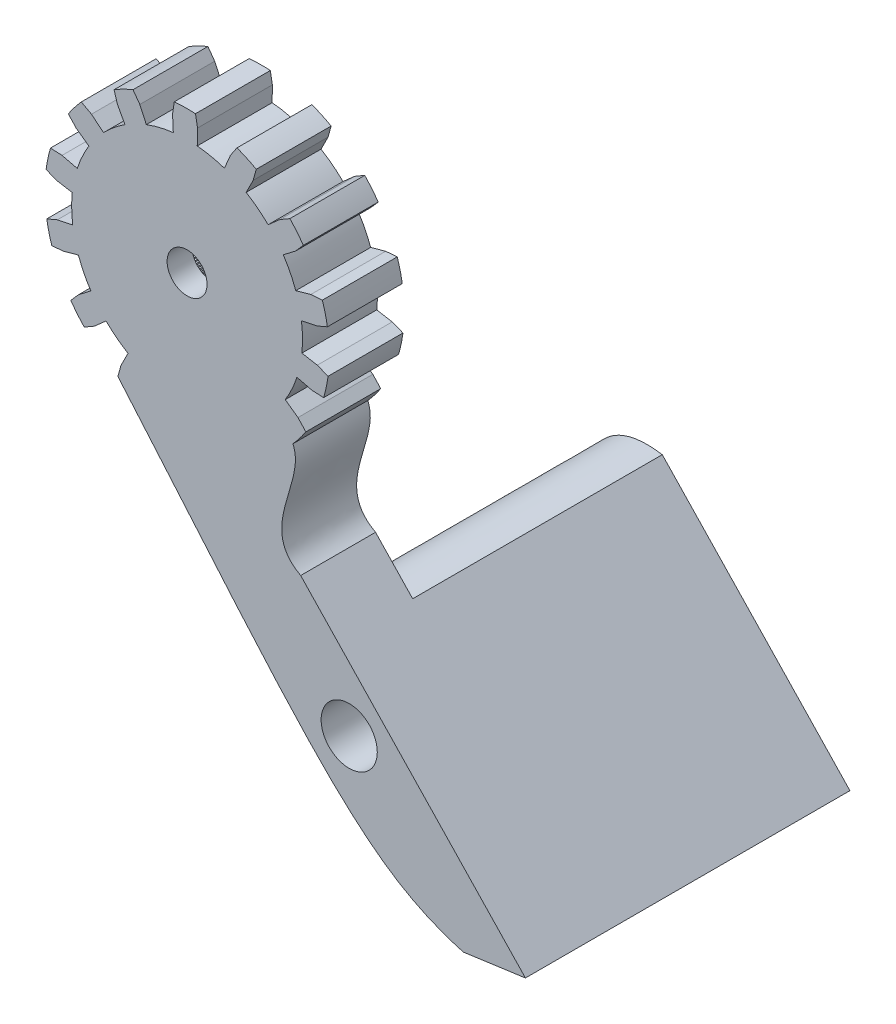
SolidWorks part; units mm, degrees
ref_plane "Front Plane" through (0, 0, 0) normal (0, 0, 1) x (1, 0, 0)
ref_plane "Top Plane" through (0, 0, 0) normal (0, 1, 0) x (1, 0, 0)
ref_plane "Right Plane" through (0, 0, 0) normal (1, 0, 0) x (0, 0, -1)
sketch "Sketch2" plane through (0, 0, 0) normal (0, 0, 1) x (1, 0, 0)
  line L0 (11.1946, 10) -> (11.1946, 10.6054) construction
  line L669 (17.6878, 7.31) -> (18.6279, 8.138)
  line L670 (18.6279, 8.138) -> (19.4304, 8.6044)
  line L671 (21.6272, -0.4657) -> (22.4922, -0.8024)
  line L672 (20.3937, -0.247) -> (21.6272, -0.4657)
  line L673 (20.3589, 1.9784) -> (21.5849, 2.2356)
  line L674 (21.5849, 2.2356) -> (22.439, 2.5991)
  line L675 (21.1094, 4.1784) -> (22.0348, 4.2505)
  line L676 (19.9032, 3.8403) -> (21.1094, 4.1784)
  line L677 (18.9062, 5.8303) -> (19.8993, 6.5939)
  line L678 (19.8993, 6.5939) -> (20.511, 7.292)
  line L679 (14.4587, -7.9329) -> (14.9822, -9.071)
  line L680 (14.9822, -9.071) -> (15.5266, -9.8227)
  line L681 (16.7705, -8.175) -> (17.0467, -9.0612)
  line L682 (16.1724, -7.0743) -> (16.7705, -8.175)
  line L683 (17.8907, -5.6595) -> (18.8561, -6.4578)
  line L684 (18.8561, -6.4578) -> (19.6729, -6.8988)
  line L685 (20.0786, -4.8746) -> (20.7119, -5.5532)
  line L686 (19.0622, -4.1424) -> (20.0786, -4.8746)
  line L687 (19.9964, -2.1222) -> (21.2126, -2.4225)
  line L688 (21.2126, -2.4225) -> (22.1398, -2.4655)
  line L689 (3.4829, -4.3861) -> (2.4899, -5.1497)
  line L690 (2.4899, -5.1497) -> (1.8781, -5.8478)
  line L691 (3.7613, -6.6939) -> (2.9588, -7.1603)
  line L692 (4.7013, -5.8658) -> (3.7613, -6.6939)
  line L693 (6.463, -7.2262) -> (5.8996, -8.3451)
  line L694 (5.8996, -8.3451) -> (5.6513, -9.2394)
  line L695 (7.7151, -9.1846) -> (7.1944, -9.953)
  line L696 (8.2027, -8.0307) -> (7.7151, -9.1846)
  line L697 (10.3802, -8.492) -> (10.3581, -9.7445)
  line L698 (10.3581, -9.7445) -> (10.5224, -10.6581)
  line L699 (12.358, -9.7133) -> (12.2223, -10.6315)
  line L700 (12.2967, -8.462) -> (12.358, -9.7133)
  line L701 (2.3105, 6.3188) -> (1.6772, 6.9974)
  line L702 (3.327, 5.5866) -> (2.3105, 6.3188)
  line L703 (2.3927, 3.5664) -> (1.1765, 3.8667)
  line L704 (1.1765, 3.8667) -> (0.2493, 3.9097)
  line L705 (0.762, 1.9099) -> (-0.103, 2.2465)
  line L706 (1.9955, 1.6912) -> (0.762, 1.9099)
  line L707 (2.0303, -0.5343) -> (0.8042, -0.7914)
  line L708 (0.8042, -0.7914) -> (-0.0498, -1.1549)
  line L709 (1.2798, -2.7343) -> (0.3543, -2.8063)
  line L710 (2.486, -2.3961) -> (1.2798, -2.7343)
  line L711 (12.009, 9.9362) -> (12.0311, 11.1887)
  line L712 (12.0311, 11.1887) -> (11.8667, 12.1023)
  line L713 (10.0311, 11.1574) -> (10.1668, 12.0757)
  line L714 (10.0924, 9.9062) -> (10.0311, 11.1574)
  line L715 (7.9305, 9.377) -> (7.4069, 10.5151)
  line L716 (7.4069, 10.5151) -> (6.8625, 11.2669)
  line L717 (5.6186, 9.6192) -> (5.3425, 10.5054)
  line L718 (6.2167, 8.5185) -> (5.6186, 9.6192)
  line L719 (4.4985, 7.1037) -> (3.533, 7.9019)
  line L720 (3.533, 7.9019) -> (2.7163, 8.343)
  line L721 (15.9262, 8.6703) -> (16.4895, 9.7892)
  line L722 (16.4895, 9.7892) -> (16.7378, 10.6836)
  line L723 (14.6741, 10.6288) -> (15.1948, 11.3972)
  line L724 (14.1864, 9.4749) -> (14.6741, 10.6288)
  arc A141 (20.511, 7.292) -> (19.4304, 8.6044) centre (11.1946, 0.7221) ccw
  arc A145 (17.6878, 7.31) -> (15.9262, 8.6703) centre (11.1946, 0.7221) ccw
  arc A149 (22.439, 2.5991) -> (22.0348, 4.2505) centre (11.1946, 0.7221) ccw
  arc A151 (22.1398, -2.4655) -> (22.4922, -0.8024) centre (11.1946, 0.7221) ccw
  arc A152 (19.6729, -6.8988) -> (20.7119, -5.5532) centre (11.1946, 0.7221) ccw
  arc A153 (15.5266, -9.8227) -> (17.0467, -9.0612) centre (11.1946, 0.7221) ccw
  arc A154 (10.5224, -10.6581) -> (12.2223, -10.6315) centre (11.1946, 0.7221) ccw
  arc A155 (5.6513, -9.2394) -> (7.1944, -9.953) centre (11.1946, 0.7221) ccw
  arc A156 (1.8781, -5.8478) -> (2.9588, -7.1603) centre (11.1946, 0.7221) ccw
  arc A157 (-0.0498, -1.1549) -> (0.3543, -2.8063) centre (11.1946, 0.7221) ccw
  arc A158 (0.2493, 3.9097) -> (-0.103, 2.2465) centre (11.1946, 0.7221) ccw
  arc A159 (2.7163, 8.343) -> (1.6772, 6.9974) centre (11.1946, 0.7221) ccw
  arc A160 (6.8625, 11.2669) -> (5.3425, 10.5054) centre (11.1946, 0.7221) ccw
  arc A161 (11.8667, 12.1023) -> (10.1668, 12.0757) centre (11.1946, 0.7221) ccw
  arc A162 (16.7378, 10.6836) -> (15.1948, 11.3972) centre (11.1946, 0.7221) ccw
  arc A163 (19.9032, 3.8403) -> (18.9062, 5.8303) centre (11.1946, 0.7221) ccw
  arc A164 (20.3937, -0.247) -> (20.3589, 1.9784) centre (11.1946, 0.7221) ccw
  arc A165 (19.0622, -4.1424) -> (19.9964, -2.1222) centre (11.1946, 0.7221) ccw
  arc A166 (16.1724, -7.0743) -> (17.8907, -5.6595) centre (11.1946, 0.7221) ccw
  arc A167 (12.2967, -8.462) -> (14.4587, -7.9329) centre (11.1946, 0.7221) ccw
  arc A168 (8.2027, -8.0307) -> (10.3802, -8.492) centre (11.1946, 0.7221) ccw
  arc A169 (4.7013, -5.8658) -> (6.463, -7.2262) centre (11.1946, 0.7221) ccw
  arc A170 (2.486, -2.3961) -> (3.4829, -4.3861) centre (11.1946, 0.7221) ccw
  arc A171 (1.9955, 1.6912) -> (2.0303, -0.5343) centre (11.1946, 0.7221) ccw
  arc A172 (3.327, 5.5866) -> (2.3927, 3.5664) centre (11.1946, 0.7221) ccw
  arc A173 (6.2167, 8.5185) -> (4.4985, 7.1037) centre (11.1946, 0.7221) ccw
  arc A174 (10.0924, 9.9062) -> (7.9305, 9.377) centre (11.1946, 0.7221) ccw
  arc A175 (14.1864, 9.4749) -> (12.009, 9.9362) centre (11.1946, 0.7221) ccw
extrude "Boss-Extrude1" add sketch "Sketch2" against normal blind 4 and the other way blind 2
sketch "Sketch3" plane through (0, 0, 2) normal (0, 0, 1) x (1, 0, 0)
  circle A0 centre (11.1946, 0) radius 3.5
  dimension "D1" = 7
extrude "Boss-Extrude2" add sketch "Sketch3" against normal blind 2
sketch "Sketch4" plane through (0, 0, 2) normal (0, 0, 1) x (1, 0, 0)
  circle A0 centre (11.1946, 0.7221) radius 4.295 construction
sketch "Sketch5" plane through (0, 0, 2) normal (0, 0, 1) x (1, 0, 0)
  line L0 (10.0276, -11.444) -> (15.4878, -11.444) construction
  line L1 (4.4176, 11.5) -> (18.1778, 11.5) construction
  line L5 (20.2959, -15.7283) -> (38.3061, -34.6532)
  line L7 (33.3336, -35.343) -> (38.3061, -34.6532)
  line L25 (15.9262, 8.6703) -> (16.4895, 9.7892)
  line L35 (3.4829, -4.3861) -> (2.4899, -5.1497)
  line L45 (15.1948, 11.3972) -> (14.6741, 10.6288)
  line L55 (14.6741, 10.6288) -> (14.1864, 9.4749)
  line L98 (22.0348, 4.2505) -> (21.1094, 4.1784)
  line L102 (12.009, 9.9362) -> (12.0311, 11.1887)
  line L104 (14.9822, -9.071) -> (15.5266, -9.8227)
  line L105 (14.9822, -9.071) -> (15.5266, -9.8227)
  line L110 (2.4899, -5.1497) -> (1.8781, -5.8478)
  line L114 (5.8996, -8.3451) -> (5.6513, -9.2394)
  line L124 (2.3927, 3.5664) -> (1.1765, 3.8667)
  line L126 (1.1765, 3.8667) -> (0.2493, 3.9097)
  line L130 (0.8042, -0.7914) -> (-0.0498, -1.1549)
  line L140 (5.3425, 10.5054) -> (5.6186, 9.6192)
  line L146 (16.4895, 9.7892) -> (16.7378, 10.6836)
  line L153 (12.0311, 11.1887) -> (11.8667, 12.1023)
  line L157 (10.1668, 12.0757) -> (10.0311, 11.1574)
  line L161 (10.0311, 11.1574) -> (10.0924, 9.9062)
  line L196 (7.9305, 9.377) -> (7.4069, 10.5151)
  line L198 (7.4069, 10.5151) -> (6.8625, 11.2669)
  line L200 (5.6186, 9.6192) -> (6.2167, 8.5185)
  line L202 (4.4985, 7.1037) -> (3.533, 7.9019)
  line L204 (3.533, 7.9019) -> (2.7163, 8.343)
  line L206 (1.6772, 6.9974) -> (2.3105, 6.3188)
  line L208 (2.3105, 6.3188) -> (3.327, 5.5866)
  line L210 (-0.103, 2.2465) -> (0.762, 1.9099)
  line L212 (0.762, 1.9099) -> (1.9955, 1.6912)
  line L214 (2.0303, -0.5343) -> (0.8042, -0.7914)
  line L216 (0.3543, -2.8063) -> (1.2798, -2.7343)
  line L218 (1.2798, -2.7343) -> (2.486, -2.3961)
  line L220 (2.9588, -7.1603) -> (3.7613, -6.6939)
  line L222 (3.7613, -6.6939) -> (4.7013, -5.8658)
  line L224 (6.463, -7.2262) -> (5.8996, -8.3451)
  line L226 (7.1944, -9.953) -> (7.7151, -9.1846)
  line L227 (7.1944, -9.953) -> (7.7151, -9.1846)
  line L228 (7.7151, -9.1846) -> (8.2027, -8.0307)
  line L229 (7.7151, -9.1846) -> (8.2027, -8.0307)
  line L230 (10.3802, -8.492) -> (10.3581, -9.7445)
  line L231 (10.3802, -8.492) -> (10.3581, -9.7445)
  line L232 (10.3581, -9.7445) -> (10.5224, -10.6581)
  line L233 (10.3581, -9.7445) -> (10.5224, -10.6581)
  line L234 (12.2223, -10.6315) -> (12.358, -9.7133)
  line L235 (12.2223, -10.6315) -> (12.358, -9.7133)
  line L236 (12.358, -9.7133) -> (12.2967, -8.462)
  line L237 (12.358, -9.7133) -> (12.2967, -8.462)
  line L238 (14.4587, -7.9329) -> (14.9822, -9.071)
  line L239 (14.4587, -7.9329) -> (14.9822, -9.071)
  line L240 (17.0467, -9.0612) -> (16.7705, -8.175)
  line L241 (17.0467, -9.0612) -> (16.7705, -8.175)
  line L242 (16.7705, -8.175) -> (16.1724, -7.0743)
  line L243 (16.7705, -8.175) -> (16.1724, -7.0743)
  line L244 (17.8907, -5.6595) -> (18.8561, -6.4578)
  line L245 (17.8907, -5.6595) -> (18.8561, -6.4578)
  line L246 (18.8561, -6.4578) -> (19.6729, -6.8988)
  line L247 (18.8561, -6.4578) -> (19.6729, -6.8988)
  line L248 (20.7119, -5.5532) -> (20.0786, -4.8746)
  line L250 (20.0786, -4.8746) -> (19.0622, -4.1424)
  line L252 (19.9964, -2.1222) -> (21.2126, -2.4225)
  line L254 (21.2126, -2.4225) -> (22.1398, -2.4655)
  line L256 (22.4922, -0.8024) -> (21.6272, -0.4657)
  line L258 (21.6272, -0.4657) -> (20.3937, -0.247)
  line L260 (20.3589, 1.9784) -> (21.5849, 2.2356)
  line L262 (21.5849, 2.2356) -> (22.439, 2.5991)
  line L264 (21.1094, 4.1784) -> (19.9032, 3.8403)
  line L266 (18.9062, 5.8303) -> (19.8993, 6.5939)
  line L268 (19.8993, 6.5939) -> (20.511, 7.292)
  line L270 (19.4304, 8.6044) -> (18.6279, 8.138)
  line L272 (18.6279, 8.138) -> (17.6878, 7.31)
  arc A14 (17.6878, 7.31) -> (15.9262, 8.6703) centre (11.1946, 0.7221) ccw
  arc A36 (16.7378, 10.6836) -> (15.1948, 11.3972) centre (11.1946, 0.7221) ccw
  arc A44 (14.1864, 9.4749) -> (12.009, 9.9362) centre (11.1946, 0.7221) ccw
  arc A52 (11.8667, 12.1023) -> (10.1668, 12.0757) centre (11.1946, 0.7221) ccw
  arc A98 (10.0924, 9.9062) -> (7.9305, 9.377) centre (11.1946, 0.7221) ccw
  arc A100 (6.8625, 11.2669) -> (5.3425, 10.5054) centre (11.1946, 0.7221) ccw
  arc A102 (6.2167, 8.5185) -> (4.4985, 7.1037) centre (11.1946, 0.7221) ccw
  arc A104 (2.7163, 8.343) -> (1.6772, 6.9974) centre (11.1946, 0.7221) ccw
  arc A106 (3.327, 5.5866) -> (2.3927, 3.5664) centre (11.1946, 0.7221) ccw
  arc A108 (0.2493, 3.9097) -> (-0.103, 2.2465) centre (11.1946, 0.7221) ccw
  arc A110 (1.9955, 1.6912) -> (2.0303, -0.5343) centre (11.1946, 0.7221) ccw
  arc A112 (-0.0498, -1.1549) -> (0.3543, -2.8063) centre (11.1946, 0.7221) ccw
  arc A114 (2.486, -2.3961) -> (3.4829, -4.3861) centre (11.1946, 0.7221) ccw
  arc A116 (1.8781, -5.8478) -> (2.9588, -7.1603) centre (11.1946, 0.7221) ccw
  arc A118 (4.7013, -5.8658) -> (6.463, -7.2262) centre (11.1946, 0.7221) ccw
  arc A120 (5.6513, -9.2394) -> (7.1944, -9.953) centre (11.1946, 0.7221) ccw
  arc A121 (5.6513, -9.2394) -> (7.1944, -9.953) centre (11.1946, 0.7221) ccw
  arc A122 (8.2027, -8.0307) -> (10.3802, -8.492) centre (11.1946, 0.7221) ccw
  arc A123 (8.2027, -8.0307) -> (10.3802, -8.492) centre (11.1946, 0.7221) ccw
  arc A124 (10.5224, -10.6581) -> (12.2223, -10.6315) centre (11.1946, 0.7221) ccw
  arc A125 (10.5224, -10.6581) -> (12.2223, -10.6315) centre (11.1946, 0.7221) ccw
  arc A126 (12.2967, -8.462) -> (14.4587, -7.9329) centre (11.1946, 0.7221) ccw
  arc A127 (12.2967, -8.462) -> (14.4587, -7.9329) centre (11.1946, 0.7221) ccw
  arc A128 (15.5266, -9.8227) -> (17.0467, -9.0612) centre (11.1946, 0.7221) ccw
  arc A129 (15.5266, -9.8227) -> (17.0467, -9.0612) centre (11.1946, 0.7221) ccw
  arc A130 (16.1724, -7.0743) -> (17.8907, -5.6595) centre (11.1946, 0.7221) ccw
  arc A131 (16.1724, -7.0743) -> (17.8907, -5.6595) centre (11.1946, 0.7221) ccw
  arc A132 (19.6729, -6.8988) -> (20.7119, -5.5532) centre (11.1946, 0.7221) ccw
  arc A134 (19.0622, -4.1424) -> (19.9964, -2.1222) centre (11.1946, 0.7221) ccw
  arc A136 (22.1398, -2.4655) -> (22.4922, -0.8024) centre (11.1946, 0.7221) ccw
  arc A138 (20.3937, -0.247) -> (20.3589, 1.9784) centre (11.1946, 0.7221) ccw
  arc A140 (22.439, 2.5991) -> (22.0348, 4.2505) centre (11.1946, 0.7221) ccw
  arc A142 (19.9032, 3.8403) -> (18.9062, 5.8303) centre (11.1946, 0.7221) ccw
  arc A144 (20.511, 7.292) -> (19.4304, 8.6044) centre (11.1946, 0.7221) ccw
  spline S0 degree 3 poles (19.6729, -6.8988) (20.7965, -9.2961) (16.694, -13.7781) (20.2959, -15.7283) knots 0 0 0 0 1 1 1 1
  spline S1 degree 3 poles (33.3336, -35.343) (25.4692, -33.1533) (21.4591, -27.7657) (5.6513, -9.2394) knots 0.222416 0.222416 0.222416 0.222416 1 1 1 1
  point P1 (18.8561, -12.3924)
  point P38 (19.8767, -15.34)
  point P40 (21.3875, -17.1208)
  point P41 (18.7424, -13.7209)
  point P42 (36.0451, -33.0139)
  point P43 (36.7278, -33.0139)
  point P44 (20.2959, -15.7283)
  point P45 (0, 0)
  point P46 (0, 0)
  point P47 (38.3061, -34.6532)
  point P51 (33.6452, -37.9896)
  point P53 (21.4947, -26.4259)
  point P54 (33.3336, -35.343)
  point P55 (23.2453, -25.9476)
  point P56 (20.2959, -26.1632)
  dimension "D1" = 0
extrude "Boss-Extrude3" add sketch "Sketch5" against normal up to surface (6 mm away) up to face at (11.1946, 0.7221, -4)
sketch "Sketch6" plane through (0, 0, -4) normal (0, 0, -1) x (-1, 0, 0)
  line L1 (-38.3061, -34.6532) -> (-20.2959, -15.7283) construction
  line L2 (-38.3061, -34.6532) -> (-23.2711, -18.8546)
  line L24 (-2.4899, -5.1497) -> (-3.4829, -4.3861)
  line L32 (-20.2959, -15.7283) -> (-38.3061, -34.6532)
  line L86 (-38.3061, -34.6532) -> (-33.3336, -35.343)
  line L88 (-38.3061, -34.6532) -> (-33.3336, -35.343)
  line L141 (-16.7378, 10.6836) -> (-16.4895, 9.7892)
  line L147 (-5.6186, 9.6192) -> (-5.3425, 10.5054)
  line L157 (0.0498, -1.1549) -> (-0.8042, -0.7914)
  line L161 (-0.2493, 3.9097) -> (-1.1765, 3.8667)
  line L163 (-1.1765, 3.8667) -> (-2.3927, 3.5664)
  line L173 (-5.6513, -9.2394) -> (-5.8996, -8.3451)
  line L177 (-1.8781, -5.8478) -> (-2.4899, -5.1497)
  line L206 (-21.1094, 4.1784) -> (-22.0348, 4.2505)
  line L208 (-17.6878, 7.31) -> (-18.6279, 8.138)
  line L210 (-18.6279, 8.138) -> (-19.4304, 8.6044)
  line L212 (-20.511, 7.292) -> (-19.8993, 6.5939)
  line L214 (-19.8993, 6.5939) -> (-18.9062, 5.8303)
  line L216 (-19.9032, 3.8403) -> (-21.1094, 4.1784)
  line L218 (-22.439, 2.5991) -> (-21.5849, 2.2356)
  line L220 (-21.5849, 2.2356) -> (-20.3589, 1.9784)
  line L222 (-20.3937, -0.247) -> (-21.6272, -0.4657)
  line L224 (-21.6272, -0.4657) -> (-22.4922, -0.8024)
  line L226 (-22.1398, -2.4655) -> (-21.2126, -2.4225)
  line L228 (-21.2126, -2.4225) -> (-19.9964, -2.1222)
  line L230 (-19.0622, -4.1424) -> (-20.0786, -4.8746)
  line L232 (-20.0786, -4.8746) -> (-20.7119, -5.5532)
  line L256 (-5.8996, -8.3451) -> (-6.463, -7.2262)
  line L258 (-4.7013, -5.8658) -> (-3.7613, -6.6939)
  line L260 (-3.7613, -6.6939) -> (-2.9588, -7.1603)
  line L262 (-2.486, -2.3961) -> (-1.2798, -2.7343)
  line L264 (-1.2798, -2.7343) -> (-0.3543, -2.8063)
  line L266 (-0.8042, -0.7914) -> (-2.0303, -0.5343)
  line L268 (-1.9955, 1.6912) -> (-0.762, 1.9099)
  line L270 (-0.762, 1.9099) -> (0.103, 2.2465)
  line L272 (-3.327, 5.5866) -> (-2.3105, 6.3188)
  line L274 (-2.3105, 6.3188) -> (-1.6772, 6.9974)
  line L276 (-2.7163, 8.343) -> (-3.533, 7.9019)
  line L278 (-3.533, 7.9019) -> (-4.4985, 7.1037)
  line L280 (-6.2167, 8.5185) -> (-5.6186, 9.6192)
  line L282 (-6.8625, 11.2669) -> (-7.4069, 10.5151)
  line L284 (-7.4069, 10.5151) -> (-7.9305, 9.377)
  line L286 (-10.0924, 9.9062) -> (-10.0311, 11.1574)
  line L288 (-10.0311, 11.1574) -> (-10.1668, 12.0757)
  line L290 (-11.8667, 12.1023) -> (-12.0311, 11.1887)
  line L292 (-12.0311, 11.1887) -> (-12.009, 9.9362)
  line L294 (-14.1864, 9.4749) -> (-14.6741, 10.6288)
  line L296 (-14.6741, 10.6288) -> (-15.1948, 11.3972)
  line L298 (-16.4895, 9.7892) -> (-15.9262, 8.6703)
  arc A44 (-15.9262, 8.6703) -> (-17.6878, 7.31) centre (-11.1946, 0.7221) ccw
  arc A85 (-19.4304, 8.6044) -> (-20.511, 7.292) centre (-11.1946, 0.7221) ccw
  arc A87 (-18.9062, 5.8303) -> (-19.9032, 3.8403) centre (-11.1946, 0.7221) ccw
  arc A89 (-22.0348, 4.2505) -> (-22.439, 2.5991) centre (-11.1946, 0.7221) ccw
  arc A91 (-20.3589, 1.9784) -> (-20.3937, -0.247) centre (-11.1946, 0.7221) ccw
  arc A93 (-22.4922, -0.8024) -> (-22.1398, -2.4655) centre (-11.1946, 0.7221) ccw
  arc A95 (-19.9964, -2.1222) -> (-19.0622, -4.1424) centre (-11.1946, 0.7221) ccw
  arc A97 (-20.7119, -5.5532) -> (-19.6729, -6.8988) centre (-11.1946, 0.7221) ccw
  arc A111 (-6.463, -7.2262) -> (-4.7013, -5.8658) centre (-11.1946, 0.7221) ccw
  arc A113 (-2.9588, -7.1603) -> (-1.8781, -5.8478) centre (-11.1946, 0.7221) ccw
  arc A115 (-3.4829, -4.3861) -> (-2.486, -2.3961) centre (-11.1946, 0.7221) ccw
  arc A117 (-0.3543, -2.8063) -> (0.0498, -1.1549) centre (-11.1946, 0.7221) ccw
  arc A119 (-2.0303, -0.5343) -> (-1.9955, 1.6912) centre (-11.1946, 0.7221) ccw
  arc A121 (0.103, 2.2465) -> (-0.2493, 3.9097) centre (-11.1946, 0.7221) ccw
  arc A123 (-2.3927, 3.5664) -> (-3.327, 5.5866) centre (-11.1946, 0.7221) ccw
  arc A125 (-1.6772, 6.9974) -> (-2.7163, 8.343) centre (-11.1946, 0.7221) ccw
  arc A127 (-4.4985, 7.1037) -> (-6.2167, 8.5185) centre (-11.1946, 0.7221) ccw
  arc A129 (-5.3425, 10.5054) -> (-6.8625, 11.2669) centre (-11.1946, 0.7221) ccw
  arc A131 (-7.9305, 9.377) -> (-10.0924, 9.9062) centre (-11.1946, 0.7221) ccw
  arc A133 (-10.1668, 12.0757) -> (-11.8667, 12.1023) centre (-11.1946, 0.7221) ccw
  arc A135 (-12.009, 9.9362) -> (-14.1864, 9.4749) centre (-11.1946, 0.7221) ccw
  arc A137 (-15.1948, 11.3972) -> (-16.7378, 10.6836) centre (-11.1946, 0.7221) ccw
  spline S1 degree 3 poles (3095.3145, 2513.7316) (-3152.5377, -2225.239) (3257.3003, 1866.3624) (-3659.2624, -1714.1694) knots -3.676611 -3.676611 -3.676611 -3.676611 5.530605 5.530605 5.530605 5.530605 only from (-5.6513, -9.2394) to (-33.3336, -35.343) construction
  spline S3 degree 3 poles (-17.1172, -22.6359) (-24.2126, -30.7109) (-27.8289, -33.8103) (-33.3336, -35.343) knots 0.455733 0.455733 0.455733 0.455733 1 1 1 1
  spline S4 degree 2 poles (-17.1172, -22.6359) (-18.6565, -18.1405) (-23.2711, -18.8546) knots 0 0 0 1 1 1
  spline S6 degree 3 poles (928.9961, -323.1558) (-986.7592, 351.2189) (950.6356, -365.5096) (-975.1186, 281.4128) knots -3.799895 -3.799895 -3.799895 -3.799895 4.619147 4.619147 4.619147 4.619147 only from (-19.6729, -6.8988) to (-20.2959, -15.7283)
  spline S7 degree 3 poles (-969.9828, -385.6106) (744.6842, 387.8248) (-748.6875, -572.1614) (734.9995, 662.636) knots -2.545715 -2.545715 -2.545715 -2.545715 3.160411 3.160411 3.160411 3.160411 only from (-33.3336, -35.343) to (-5.6513, -9.2394)
  point P13 (-23.2711, -18.8546)
  point P18 (-18.5006, -18.6285)
  point P19 (-17.1172, -22.6359)
  point P20 (-19.5567, -19.3653)
  dimension "D1" = 0
extrude "Boss-Extrude4" add sketch "Sketch6" along normal blind 20
sketch "Sketch7" plane through (0, 0, -4) normal (0, 0, -1) x (-1, 0, 0)
  line L200 (-9.7843, 3.3038) -> (-9.9297, 3.2201)
  line L201 (-9.7763, 3.1362) -> (-9.7843, 3.3038)
  line L202 (-9.6259, 3.2107) -> (-9.7763, 3.1362)
  line L203 (-9.6285, 3.0429) -> (-9.6259, 3.2107)
  line L204 (-9.4737, 3.1077) -> (-9.6285, 3.0429)
  line L205 (-9.4868, 2.9405) -> (-9.4737, 3.1077)
  line L206 (-9.3283, 2.9955) -> (-9.4868, 2.9405)
  line L207 (-9.3518, 2.8293) -> (-9.3283, 2.9955)
  line L208 (-9.1901, 2.8743) -> (-9.3518, 2.8293)
  line L209 (-9.2241, 2.7099) -> (-9.1901, 2.8743)
  line L210 (-9.0599, 2.7446) -> (-9.2241, 2.7099)
  line L211 (-9.1041, 2.5828) -> (-9.0599, 2.7446)
  line L212 (-8.9381, 2.6071) -> (-9.1041, 2.5828)
  line L213 (-8.9923, 2.4483) -> (-8.9381, 2.6071)
  line L214 (-8.8251, 2.4622) -> (-8.9923, 2.4483)
  line L215 (-8.8892, 2.3071) -> (-8.8251, 2.4622)
  line L216 (-8.7215, 2.3104) -> (-8.8892, 2.3071)
  line L217 (-8.7952, 2.1597) -> (-8.7215, 2.3104)
  line L218 (-8.6276, 2.1525) -> (-8.7952, 2.1597)
  line L219 (-8.7106, 2.0067) -> (-8.6276, 2.1525)
  line L220 (-8.5438, 1.9889) -> (-8.7106, 2.0067)
  line L221 (-8.6358, 1.8487) -> (-8.5438, 1.9889)
  line L222 (-8.4704, 1.8205) -> (-8.6358, 1.8487)
  line L223 (-8.571, 1.6862) -> (-8.4704, 1.8205)
  line L224 (-8.4077, 1.6477) -> (-8.571, 1.6862)
  line L225 (-8.5166, 1.5201) -> (-8.4077, 1.6477)
  line L226 (-8.3561, 1.4714) -> (-8.5166, 1.5201)
  line L227 (-8.4727, 1.3508) -> (-8.3561, 1.4714)
  line L228 (-8.3156, 1.2922) -> (-8.4727, 1.3508)
  line L229 (-8.4396, 1.1792) -> (-8.3156, 1.2922)
  line L230 (-8.2864, 1.1108) -> (-8.4396, 1.1792)
  line L231 (-8.4173, 1.0058) -> (-8.2864, 1.1108)
  line L232 (-8.2687, 0.9279) -> (-8.4173, 1.0058)
  line L233 (-8.4059, 0.8313) -> (-8.2687, 0.9279)
  line L234 (-8.2625, 0.7442) -> (-8.4059, 0.8313)
  line L235 (-8.4055, 0.6565) -> (-8.2625, 0.7442)
  line L236 (-8.2678, 0.5605) -> (-8.4055, 0.6565)
  line L237 (-8.416, 0.4819) -> (-8.2678, 0.5605)
  line L238 (-8.2847, 0.3776) -> (-8.416, 0.4819)
  line L239 (-8.4375, 0.3084) -> (-8.2847, 0.3776)
  line L240 (-8.313, 0.196) -> (-8.4375, 0.3084)
  line L241 (-8.4699, 0.1366) -> (-8.313, 0.196)
  line L242 (-8.3527, 0.0166) -> (-8.4699, 0.1366)
  line L243 (-8.513, -0.0328) -> (-8.3527, 0.0166)
  line L244 (-8.4035, -0.16) -> (-8.513, -0.0328)
  line L245 (-8.5666, -0.1993) -> (-8.4035, -0.16)
  line L246 (-8.4653, -0.333) -> (-8.5666, -0.1993)
  line L247 (-8.6306, -0.362) -> (-8.4653, -0.333)
  line L248 (-8.5379, -0.5018) -> (-8.6306, -0.362)
  line L249 (-8.7047, -0.5203) -> (-8.5379, -0.5018)
  line L250 (-8.621, -0.6657) -> (-8.7047, -0.5203)
  line L251 (-8.7886, -0.6738) -> (-8.621, -0.6657)
  line L252 (-8.7141, -0.8241) -> (-8.7886, -0.6738)
  line L253 (-8.8819, -0.8216) -> (-8.7141, -0.8241)
  line L254 (-8.8171, -0.9763) -> (-8.8819, -0.8216)
  line L255 (-8.9843, -0.9633) -> (-8.8171, -0.9763)
  line L256 (-8.9293, -1.1218) -> (-8.9843, -0.9633)
  line L257 (-9.0955, -1.0983) -> (-8.9293, -1.1218)
  line L258 (-9.0505, -1.2599) -> (-9.0955, -1.0983)
  line L259 (-9.2148, -1.226) -> (-9.0505, -1.2599)
  line L260 (-9.1802, -1.3901) -> (-9.2148, -1.226)
  line L261 (-9.342, -1.346) -> (-9.1802, -1.3901)
  line L262 (-9.3177, -1.512) -> (-9.342, -1.346)
  line L263 (-9.4765, -1.4577) -> (-9.3177, -1.512)
  line L264 (-9.4626, -1.6249) -> (-9.4765, -1.4577)
  line L265 (-9.6177, -1.5608) -> (-9.4626, -1.6249)
  line L266 (-9.6144, -1.7286) -> (-9.6177, -1.5608)
  line L267 (-9.7651, -1.6549) -> (-9.6144, -1.7286)
  line L268 (-9.7723, -1.8225) -> (-9.7651, -1.6549)
  line L269 (-9.9181, -1.7395) -> (-9.7723, -1.8225)
  line L270 (-9.9358, -1.9063) -> (-9.9181, -1.7395)
  line L271 (-10.0761, -1.8143) -> (-9.9358, -1.9063)
  line L272 (-10.1043, -1.9797) -> (-10.0761, -1.8143)
  line L273 (-10.2385, -1.879) -> (-10.1043, -1.9797)
  line L274 (-10.2771, -2.0423) -> (-10.2385, -1.879)
  line L275 (-10.4047, -1.9334) -> (-10.2771, -2.0423)
  line L276 (-10.4534, -2.094) -> (-10.4047, -1.9334)
  line L277 (-10.5739, -1.9773) -> (-10.4534, -2.094)
  line L278 (-10.6326, -2.1345) -> (-10.5739, -1.9773)
  line L279 (-10.7456, -2.0105) -> (-10.6326, -2.1345)
  line L280 (-10.814, -2.1637) -> (-10.7456, -2.0105)
  line L281 (-10.919, -2.0328) -> (-10.814, -2.1637)
  line L282 (-10.9969, -2.1814) -> (-10.919, -2.0328)
  line L283 (-11.0935, -2.0442) -> (-10.9969, -2.1814)
  line L284 (-11.1806, -2.1876) -> (-11.0935, -2.0442)
  line L285 (-11.2683, -2.0446) -> (-11.1806, -2.1876)
  line L286 (-11.3643, -2.1822) -> (-11.2683, -2.0446)
  line L287 (-11.4429, -2.034) -> (-11.3643, -2.1822)
  line L288 (-11.5472, -2.1654) -> (-11.4429, -2.034)
  line L289 (-11.6164, -2.0125) -> (-11.5472, -2.1654)
  line L290 (-11.7288, -2.1371) -> (-11.6164, -2.0125)
  line L291 (-11.7882, -1.9802) -> (-11.7288, -2.1371)
  line L292 (-11.9082, -2.0974) -> (-11.7882, -1.9802)
  line L293 (-11.9576, -1.9371) -> (-11.9082, -2.0974)
  line L294 (-12.0848, -2.0465) -> (-11.9576, -1.9371)
  line L295 (-12.1241, -1.8834) -> (-12.0848, -2.0465)
  line L296 (-12.2578, -1.9847) -> (-12.1241, -1.8834)
  line L297 (-12.2868, -1.8194) -> (-12.2578, -1.9847)
  line L298 (-12.4266, -1.9121) -> (-12.2868, -1.8194)
  line L299 (-12.4451, -1.7454) -> (-12.4266, -1.9121)
  line L300 (-12.5905, -1.8291) -> (-12.4451, -1.7454)
  line L301 (-12.5985, -1.6615) -> (-12.5905, -1.8291)
  line L302 (-12.7489, -1.7359) -> (-12.5985, -1.6615)
  line L303 (-12.7464, -1.5682) -> (-12.7489, -1.7359)
  line L304 (-12.9011, -1.633) -> (-12.7464, -1.5682)
  line L305 (-12.8881, -1.4657) -> (-12.9011, -1.633)
  line L306 (-13.0466, -1.5207) -> (-12.8881, -1.4657)
  line L307 (-13.0231, -1.3546) -> (-13.0466, -1.5207)
  line L308 (-13.1847, -1.3995) -> (-13.0231, -1.3546)
  line L309 (-13.1508, -1.2352) -> (-13.1847, -1.3995)
  line L310 (-13.3149, -1.2699) -> (-13.1508, -1.2352)
  line L311 (-13.2708, -1.108) -> (-13.3149, -1.2699)
  line L312 (-13.4368, -1.1323) -> (-13.2708, -1.108)
  line L313 (-13.3825, -0.9736) -> (-13.4368, -1.1323)
  line L314 (-13.5497, -0.9874) -> (-13.3825, -0.9736)
  line L315 (-13.4856, -0.8324) -> (-13.5497, -0.9874)
  line L316 (-13.6534, -0.8357) -> (-13.4856, -0.8324)
  line L317 (-13.5797, -0.685) -> (-13.6534, -0.8357)
  line L318 (-13.7473, -0.6777) -> (-13.5797, -0.685)
  line L319 (-13.6643, -0.5319) -> (-13.7473, -0.6777)
  line L320 (-13.8311, -0.5142) -> (-13.6643, -0.5319)
  line L321 (-13.7391, -0.3739) -> (-13.8311, -0.5142)
  line L322 (-13.9045, -0.3457) -> (-13.7391, -0.3739)
  line L323 (-13.8038, -0.2115) -> (-13.9045, -0.3457)
  line L324 (-13.9671, -0.173) -> (-13.8038, -0.2115)
  line L325 (-13.8582, -0.0453) -> (-13.9671, -0.173)
  line L326 (-14.0188, 0.0033) -> (-13.8582, -0.0453)
  line L327 (-13.9021, 0.1239) -> (-14.0188, 0.0033)
  line L328 (-14.0593, 0.1826) -> (-13.9021, 0.1239)
  line L329 (-13.9353, 0.2956) -> (-14.0593, 0.1826)
  line L330 (-14.0885, 0.364) -> (-13.9353, 0.2956)
  line L331 (-13.9576, 0.469) -> (-14.0885, 0.364)
  line L332 (-14.1062, 0.5469) -> (-13.9576, 0.469)
  line L333 (-13.969, 0.6434) -> (-14.1062, 0.5469)
  line L334 (-14.1124, 0.7305) -> (-13.969, 0.6434)
  line L335 (-13.9694, 0.8183) -> (-14.1124, 0.7305)
  line L336 (-14.107, 0.9142) -> (-13.9694, 0.8183)
  line L337 (-13.9588, 0.9928) -> (-14.107, 0.9142)
  line L338 (-14.0902, 1.0972) -> (-13.9588, 0.9928)
  line L339 (-13.9373, 1.1663) -> (-14.0902, 1.0972)
  line L340 (-14.0619, 1.2787) -> (-13.9373, 1.1663)
  line L341 (-13.9049, 1.3381) -> (-14.0619, 1.2787)
  line L342 (-14.0222, 1.4582) -> (-13.9049, 1.3381)
  line L343 (-13.8619, 1.5076) -> (-14.0222, 1.4582)
  line L344 (-13.9713, 1.6347) -> (-13.8619, 1.5076)
  line L345 (-13.8082, 1.674) -> (-13.9713, 1.6347)
  line L346 (-13.9095, 1.8078) -> (-13.8082, 1.674)
  line L347 (-13.7442, 1.8367) -> (-13.9095, 1.8078)
  line L348 (-13.8369, 1.9766) -> (-13.7442, 1.8367)
  line L349 (-13.6702, 1.9951) -> (-13.8369, 1.9766)
  line L350 (-13.7539, 2.1405) -> (-13.6702, 1.9951)
  line L351 (-13.5863, 2.1485) -> (-13.7539, 2.1405)
  line L352 (-13.6607, 2.2989) -> (-13.5863, 2.1485)
  line L353 (-13.493, 2.2963) -> (-13.6607, 2.2989)
  line L354 (-13.5578, 2.4511) -> (-13.493, 2.2963)
  line L355 (-13.3905, 2.438) -> (-13.5578, 2.4511)
  line L356 (-13.4455, 2.5965) -> (-13.3905, 2.438)
  line L357 (-13.2794, 2.573) -> (-13.4455, 2.5965)
  line L358 (-13.3243, 2.7347) -> (-13.2794, 2.573)
  line L359 (-13.16, 2.7007) -> (-13.3243, 2.7347)
  line L360 (-13.1947, 2.8649) -> (-13.16, 2.7007)
  line L361 (-13.0328, 2.8207) -> (-13.1947, 2.8649)
  line L362 (-13.0571, 2.9867) -> (-13.0328, 2.8207)
  line L363 (-12.8984, 2.9325) -> (-13.0571, 2.9867)
  line L364 (-12.9122, 3.0997) -> (-12.8984, 2.9325)
  line L365 (-12.7572, 3.0356) -> (-12.9122, 3.0997)
  line L366 (-12.7605, 3.2033) -> (-12.7572, 3.0356)
  line L367 (-12.6098, 3.1296) -> (-12.7605, 3.2033)
  line L368 (-12.6025, 3.2972) -> (-12.6098, 3.1296)
  line L369 (-12.4567, 3.2142) -> (-12.6025, 3.2972)
  line L370 (-12.439, 3.381) -> (-12.4567, 3.2142)
  line L371 (-12.2987, 3.289) -> (-12.439, 3.381)
  line L372 (-12.2705, 3.4544) -> (-12.2987, 3.289)
  line L373 (-12.1363, 3.3538) -> (-12.2705, 3.4544)
  line L374 (-12.0978, 3.5171) -> (-12.1363, 3.3538)
  line L375 (-11.9701, 3.4082) -> (-12.0978, 3.5171)
  line L376 (-11.9215, 3.5687) -> (-11.9701, 3.4082)
  line L377 (-11.8009, 3.4521) -> (-11.9215, 3.5687)
  line L378 (-11.7422, 3.6092) -> (-11.8009, 3.4521)
  line L379 (-11.6292, 3.4852) -> (-11.7422, 3.6092)
  line L380 (-11.5608, 3.6384) -> (-11.6292, 3.4852)
  line L381 (-11.4558, 3.5075) -> (-11.5608, 3.6384)
  line L382 (-11.3779, 3.6561) -> (-11.4558, 3.5075)
  line L383 (-11.2814, 3.5189) -> (-11.3779, 3.6561)
  line L384 (-11.1943, 3.6623) -> (-11.2814, 3.5189)
  line L385 (-11.1065, 3.5193) -> (-11.1943, 3.6623)
  line L386 (-11.0106, 3.657) -> (-11.1065, 3.5193)
  line L387 (-10.932, 3.5088) -> (-11.0106, 3.657)
  line L388 (-10.8276, 3.6401) -> (-10.932, 3.5088)
  line L389 (-10.7585, 3.4873) -> (-10.8276, 3.6401)
  line L390 (-10.6461, 3.6118) -> (-10.7585, 3.4873)
  line L391 (-10.5867, 3.4549) -> (-10.6461, 3.6118)
  line L392 (-10.4666, 3.5721) -> (-10.5867, 3.4549)
  line L393 (-10.4172, 3.4118) -> (-10.4666, 3.5721)
  line L394 (-10.2901, 3.5213) -> (-10.4172, 3.4118)
  line L395 (-10.2508, 3.3582) -> (-10.2901, 3.5213)
  line L396 (-10.117, 3.4594) -> (-10.2508, 3.3582)
  line L397 (-10.0881, 3.2942) -> (-10.117, 3.4594)
  line L398 (-9.9482, 3.3869) -> (-10.0881, 3.2942)
  line L399 (-9.9297, 3.2201) -> (-9.9482, 3.3869)
  line L400 (-9.7843, 3.3038) -> (-9.9297, 3.2201)
  line L401 (-9.7763, 3.1362) -> (-9.7843, 3.3038)
  line L402 (-9.6259, 3.2107) -> (-9.7763, 3.1362)
  line L403 (-9.6285, 3.0429) -> (-9.6259, 3.2107)
  line L404 (-9.4737, 3.1077) -> (-9.6285, 3.0429)
  line L405 (-9.4868, 2.9405) -> (-9.4737, 3.1077)
  line L406 (-9.3283, 2.9955) -> (-9.4868, 2.9405)
  line L407 (-9.3518, 2.8293) -> (-9.3283, 2.9955)
  line L408 (-9.1901, 2.8743) -> (-9.3518, 2.8293)
  line L409 (-9.2241, 2.7099) -> (-9.1901, 2.8743)
  line L410 (-9.0599, 2.7446) -> (-9.2241, 2.7099)
  line L411 (-9.1041, 2.5828) -> (-9.0599, 2.7446)
  line L412 (-8.9381, 2.6071) -> (-9.1041, 2.5828)
  line L413 (-8.9923, 2.4483) -> (-8.9381, 2.6071)
  line L414 (-8.8251, 2.4622) -> (-8.9923, 2.4483)
  line L415 (-8.8892, 2.3071) -> (-8.8251, 2.4622)
  line L416 (-8.7215, 2.3104) -> (-8.8892, 2.3071)
  line L417 (-8.7952, 2.1597) -> (-8.7215, 2.3104)
  line L418 (-8.6276, 2.1525) -> (-8.7952, 2.1597)
  line L419 (-8.7106, 2.0067) -> (-8.6276, 2.1525)
  line L420 (-8.5438, 1.9889) -> (-8.7106, 2.0067)
  line L421 (-8.6358, 1.8487) -> (-8.5438, 1.9889)
  line L422 (-8.4704, 1.8205) -> (-8.6358, 1.8487)
  line L423 (-8.571, 1.6862) -> (-8.4704, 1.8205)
  line L424 (-8.4077, 1.6477) -> (-8.571, 1.6862)
  line L425 (-8.5166, 1.5201) -> (-8.4077, 1.6477)
  line L426 (-8.3561, 1.4714) -> (-8.5166, 1.5201)
  line L427 (-8.4727, 1.3508) -> (-8.3561, 1.4714)
  line L428 (-8.3156, 1.2922) -> (-8.4727, 1.3508)
  line L429 (-8.4396, 1.1792) -> (-8.3156, 1.2922)
  line L430 (-8.2864, 1.1108) -> (-8.4396, 1.1792)
  line L431 (-8.4173, 1.0058) -> (-8.2864, 1.1108)
  line L432 (-8.2687, 0.9279) -> (-8.4173, 1.0058)
  line L433 (-8.4059, 0.8313) -> (-8.2687, 0.9279)
  line L434 (-8.2625, 0.7442) -> (-8.4059, 0.8313)
  line L435 (-8.4055, 0.6565) -> (-8.2625, 0.7442)
  line L436 (-8.2678, 0.5605) -> (-8.4055, 0.6565)
  line L437 (-8.416, 0.4819) -> (-8.2678, 0.5605)
  line L438 (-8.2847, 0.3776) -> (-8.416, 0.4819)
  line L439 (-8.4375, 0.3084) -> (-8.2847, 0.3776)
  line L440 (-8.313, 0.196) -> (-8.4375, 0.3084)
  line L441 (-8.4699, 0.1366) -> (-8.313, 0.196)
  line L442 (-8.3527, 0.0166) -> (-8.4699, 0.1366)
  line L443 (-8.513, -0.0328) -> (-8.3527, 0.0166)
  line L444 (-8.4035, -0.16) -> (-8.513, -0.0328)
  line L445 (-8.5666, -0.1993) -> (-8.4035, -0.16)
  line L446 (-8.4653, -0.333) -> (-8.5666, -0.1993)
  line L447 (-8.6306, -0.362) -> (-8.4653, -0.333)
  line L448 (-8.5379, -0.5018) -> (-8.6306, -0.362)
  line L449 (-8.7047, -0.5203) -> (-8.5379, -0.5018)
  line L450 (-8.621, -0.6657) -> (-8.7047, -0.5203)
  line L451 (-8.7886, -0.6738) -> (-8.621, -0.6657)
  line L452 (-8.7141, -0.8241) -> (-8.7886, -0.6738)
  line L453 (-8.8819, -0.8216) -> (-8.7141, -0.8241)
  line L454 (-8.8171, -0.9763) -> (-8.8819, -0.8216)
  line L455 (-8.9843, -0.9633) -> (-8.8171, -0.9763)
  line L456 (-8.9293, -1.1218) -> (-8.9843, -0.9633)
  line L457 (-9.0955, -1.0983) -> (-8.9293, -1.1218)
  line L458 (-9.0505, -1.2599) -> (-9.0955, -1.0983)
  line L459 (-9.2148, -1.226) -> (-9.0505, -1.2599)
  line L460 (-9.1802, -1.3901) -> (-9.2148, -1.226)
  line L461 (-9.342, -1.346) -> (-9.1802, -1.3901)
  line L462 (-9.3177, -1.512) -> (-9.342, -1.346)
  line L463 (-9.4765, -1.4577) -> (-9.3177, -1.512)
  line L464 (-9.4626, -1.6249) -> (-9.4765, -1.4577)
  line L465 (-9.6177, -1.5608) -> (-9.4626, -1.6249)
  line L466 (-9.6144, -1.7286) -> (-9.6177, -1.5608)
  line L467 (-9.7651, -1.6549) -> (-9.6144, -1.7286)
  line L468 (-9.7723, -1.8225) -> (-9.7651, -1.6549)
  line L469 (-9.9181, -1.7395) -> (-9.7723, -1.8225)
  line L470 (-9.9358, -1.9063) -> (-9.9181, -1.7395)
  line L471 (-10.0761, -1.8143) -> (-9.9358, -1.9063)
  line L472 (-10.1043, -1.9797) -> (-10.0761, -1.8143)
  line L473 (-10.2385, -1.879) -> (-10.1043, -1.9797)
  line L474 (-10.2771, -2.0423) -> (-10.2385, -1.879)
  line L475 (-10.4047, -1.9334) -> (-10.2771, -2.0423)
  line L476 (-10.4534, -2.094) -> (-10.4047, -1.9334)
  line L477 (-10.5739, -1.9773) -> (-10.4534, -2.094)
  line L478 (-10.6326, -2.1345) -> (-10.5739, -1.9773)
  line L479 (-10.7456, -2.0105) -> (-10.6326, -2.1345)
  line L480 (-10.814, -2.1637) -> (-10.7456, -2.0105)
  line L481 (-10.919, -2.0328) -> (-10.814, -2.1637)
  line L482 (-10.9969, -2.1814) -> (-10.919, -2.0328)
  line L483 (-11.0935, -2.0442) -> (-10.9969, -2.1814)
  line L484 (-11.1806, -2.1876) -> (-11.0935, -2.0442)
  line L485 (-11.2683, -2.0446) -> (-11.1806, -2.1876)
  line L486 (-11.3643, -2.1822) -> (-11.2683, -2.0446)
  line L487 (-11.4429, -2.034) -> (-11.3643, -2.1822)
  line L488 (-11.5472, -2.1654) -> (-11.4429, -2.034)
  line L489 (-11.6164, -2.0125) -> (-11.5472, -2.1654)
  line L490 (-11.7288, -2.1371) -> (-11.6164, -2.0125)
  line L491 (-11.7882, -1.9802) -> (-11.7288, -2.1371)
  line L492 (-11.9082, -2.0974) -> (-11.7882, -1.9802)
  line L493 (-11.9576, -1.9371) -> (-11.9082, -2.0974)
  line L494 (-12.0848, -2.0465) -> (-11.9576, -1.9371)
  line L495 (-12.1241, -1.8834) -> (-12.0848, -2.0465)
  line L496 (-12.2578, -1.9847) -> (-12.1241, -1.8834)
  line L497 (-12.2868, -1.8194) -> (-12.2578, -1.9847)
  line L498 (-12.4266, -1.9121) -> (-12.2868, -1.8194)
  line L499 (-12.4451, -1.7454) -> (-12.4266, -1.9121)
  line L500 (-12.5905, -1.8291) -> (-12.4451, -1.7454)
  line L501 (-12.5985, -1.6615) -> (-12.5905, -1.8291)
  line L502 (-12.7489, -1.7359) -> (-12.5985, -1.6615)
  line L503 (-12.7464, -1.5682) -> (-12.7489, -1.7359)
  line L504 (-12.9011, -1.633) -> (-12.7464, -1.5682)
  line L505 (-12.8881, -1.4657) -> (-12.9011, -1.633)
  line L506 (-13.0466, -1.5207) -> (-12.8881, -1.4657)
  line L507 (-13.0231, -1.3546) -> (-13.0466, -1.5207)
  line L508 (-13.1847, -1.3995) -> (-13.0231, -1.3546)
  line L509 (-13.1508, -1.2352) -> (-13.1847, -1.3995)
  line L510 (-13.3149, -1.2699) -> (-13.1508, -1.2352)
  line L511 (-13.2708, -1.108) -> (-13.3149, -1.2699)
  line L512 (-13.4368, -1.1323) -> (-13.2708, -1.108)
  line L513 (-13.3825, -0.9736) -> (-13.4368, -1.1323)
  line L514 (-13.5497, -0.9874) -> (-13.3825, -0.9736)
  line L515 (-13.4856, -0.8324) -> (-13.5497, -0.9874)
  line L516 (-13.6534, -0.8357) -> (-13.4856, -0.8324)
  line L517 (-13.5797, -0.685) -> (-13.6534, -0.8357)
  line L518 (-13.7473, -0.6777) -> (-13.5797, -0.685)
  line L519 (-13.6643, -0.5319) -> (-13.7473, -0.6777)
  line L520 (-13.8311, -0.5142) -> (-13.6643, -0.5319)
  line L521 (-13.7391, -0.3739) -> (-13.8311, -0.5142)
  line L522 (-13.9045, -0.3457) -> (-13.7391, -0.3739)
  line L523 (-13.8038, -0.2115) -> (-13.9045, -0.3457)
  line L524 (-13.9671, -0.173) -> (-13.8038, -0.2115)
  line L525 (-13.8582, -0.0453) -> (-13.9671, -0.173)
  line L526 (-14.0188, 0.0033) -> (-13.8582, -0.0453)
  line L527 (-13.9021, 0.1239) -> (-14.0188, 0.0033)
  line L528 (-14.0593, 0.1826) -> (-13.9021, 0.1239)
  line L529 (-13.9353, 0.2956) -> (-14.0593, 0.1826)
  line L530 (-14.0885, 0.364) -> (-13.9353, 0.2956)
  line L531 (-13.9576, 0.469) -> (-14.0885, 0.364)
  line L532 (-14.1062, 0.5469) -> (-13.9576, 0.469)
  line L533 (-13.969, 0.6434) -> (-14.1062, 0.5469)
  line L534 (-14.1124, 0.7305) -> (-13.969, 0.6434)
  line L535 (-13.9694, 0.8183) -> (-14.1124, 0.7305)
  line L536 (-14.107, 0.9142) -> (-13.9694, 0.8183)
  line L537 (-13.9588, 0.9928) -> (-14.107, 0.9142)
  line L538 (-14.0902, 1.0972) -> (-13.9588, 0.9928)
  line L539 (-13.9373, 1.1663) -> (-14.0902, 1.0972)
  line L540 (-14.0619, 1.2787) -> (-13.9373, 1.1663)
  line L541 (-13.9049, 1.3381) -> (-14.0619, 1.2787)
  line L542 (-14.0222, 1.4582) -> (-13.9049, 1.3381)
  line L543 (-13.8619, 1.5076) -> (-14.0222, 1.4582)
  line L544 (-13.9713, 1.6347) -> (-13.8619, 1.5076)
  line L545 (-13.8082, 1.674) -> (-13.9713, 1.6347)
  line L546 (-13.9095, 1.8078) -> (-13.8082, 1.674)
  line L547 (-13.7442, 1.8367) -> (-13.9095, 1.8078)
  line L548 (-13.8369, 1.9766) -> (-13.7442, 1.8367)
  line L549 (-13.6702, 1.9951) -> (-13.8369, 1.9766)
  line L550 (-13.7539, 2.1405) -> (-13.6702, 1.9951)
  line L551 (-13.5863, 2.1485) -> (-13.7539, 2.1405)
  line L552 (-13.6607, 2.2989) -> (-13.5863, 2.1485)
  line L553 (-13.493, 2.2963) -> (-13.6607, 2.2989)
  line L554 (-13.5578, 2.4511) -> (-13.493, 2.2963)
  line L555 (-13.3905, 2.438) -> (-13.5578, 2.4511)
  line L556 (-13.4455, 2.5965) -> (-13.3905, 2.438)
  line L557 (-13.2794, 2.573) -> (-13.4455, 2.5965)
  line L558 (-13.3243, 2.7347) -> (-13.2794, 2.573)
  line L559 (-13.16, 2.7007) -> (-13.3243, 2.7347)
  line L560 (-13.1947, 2.8649) -> (-13.16, 2.7007)
  line L561 (-13.0328, 2.8207) -> (-13.1947, 2.8649)
  line L562 (-13.0571, 2.9867) -> (-13.0328, 2.8207)
  line L563 (-12.8984, 2.9325) -> (-13.0571, 2.9867)
  line L564 (-12.9122, 3.0997) -> (-12.8984, 2.9325)
  line L565 (-12.7572, 3.0356) -> (-12.9122, 3.0997)
  line L566 (-12.7605, 3.2033) -> (-12.7572, 3.0356)
  line L567 (-12.6098, 3.1296) -> (-12.7605, 3.2033)
  line L568 (-12.6025, 3.2972) -> (-12.6098, 3.1296)
  line L569 (-12.4567, 3.2142) -> (-12.6025, 3.2972)
  line L570 (-12.439, 3.381) -> (-12.4567, 3.2142)
  line L571 (-12.2987, 3.289) -> (-12.439, 3.381)
  line L572 (-12.2705, 3.4544) -> (-12.2987, 3.289)
  line L573 (-12.1363, 3.3538) -> (-12.2705, 3.4544)
  line L574 (-12.0978, 3.5171) -> (-12.1363, 3.3538)
  line L575 (-11.9701, 3.4082) -> (-12.0978, 3.5171)
  line L576 (-11.9215, 3.5687) -> (-11.9701, 3.4082)
  line L577 (-11.8009, 3.4521) -> (-11.9215, 3.5687)
  line L578 (-11.7422, 3.6092) -> (-11.8009, 3.4521)
  line L579 (-11.6292, 3.4852) -> (-11.7422, 3.6092)
  line L580 (-11.5608, 3.6384) -> (-11.6292, 3.4852)
  line L581 (-11.4558, 3.5075) -> (-11.5608, 3.6384)
  line L582 (-11.3779, 3.6561) -> (-11.4558, 3.5075)
  line L583 (-11.2814, 3.5189) -> (-11.3779, 3.6561)
  line L584 (-11.1943, 3.6623) -> (-11.2814, 3.5189)
  line L585 (-11.1065, 3.5193) -> (-11.1943, 3.6623)
  line L586 (-11.0106, 3.657) -> (-11.1065, 3.5193)
  line L587 (-10.932, 3.5088) -> (-11.0106, 3.657)
  line L588 (-10.8276, 3.6401) -> (-10.932, 3.5088)
  line L589 (-10.7585, 3.4873) -> (-10.8276, 3.6401)
  line L590 (-10.6461, 3.6118) -> (-10.7585, 3.4873)
  line L591 (-10.5867, 3.4549) -> (-10.6461, 3.6118)
  line L592 (-10.4666, 3.5721) -> (-10.5867, 3.4549)
  line L593 (-10.4172, 3.4118) -> (-10.4666, 3.5721)
  line L594 (-10.2901, 3.5213) -> (-10.4172, 3.4118)
  line L595 (-10.2508, 3.3582) -> (-10.2901, 3.5213)
  line L596 (-10.117, 3.4594) -> (-10.2508, 3.3582)
  line L597 (-10.0881, 3.2942) -> (-10.117, 3.4594)
  line L598 (-9.9482, 3.3869) -> (-10.0881, 3.2942)
  line L599 (-9.9297, 3.2201) -> (-9.9482, 3.3869)
  dimension "D1" = 0
extrude "Cut-Extrude1" cut sketch "Sketch7" against normal offset from surface (4 mm away) 2
sketch "Sketch8" plane through (0, 0, -4) normal (0, 0, -1) x (-1, 0, 0)
  circle A0 centre (-11.1946, 0.7221) radius 1.6
  dimension "D1" = 3.2
extrude "Cut-Extrude2" cut sketch "Sketch8" against normal blind 8
sketch "Sketch9" plane through (0, 0, 2) normal (0, 0, 1) x (1, 0, 0)
  circle A1 centre (24.1857, -24.9183) radius 2.25
extrude "Cut-Extrude3" cut sketch "Sketch9" against normal through all
